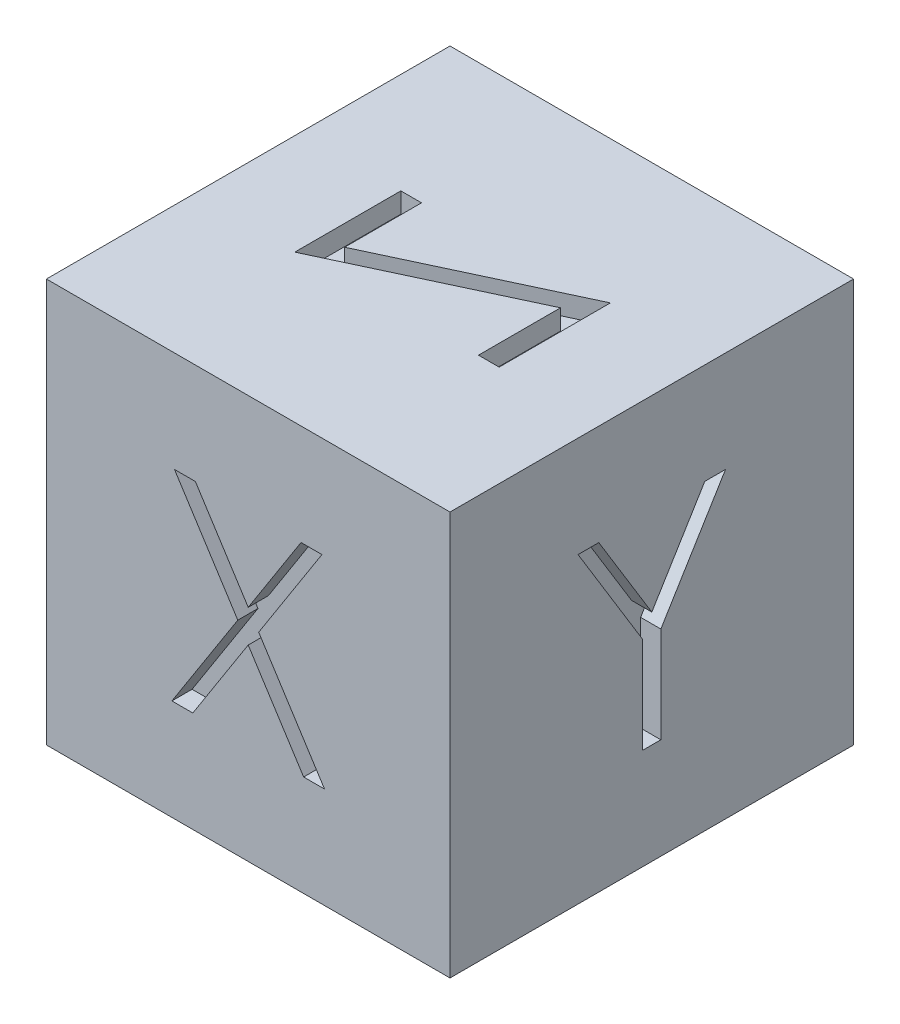
SolidWorks part; units mm, degrees
material "PET"
ref_plane "Front Plane" through (0, 0, 0) normal (0, 0, 1) x (1, 0, 0)
ref_plane "Top Plane" through (0, 0, 0) normal (0, 1, 0) x (1, 0, 0)
ref_plane "Right Plane" through (0, 0, 0) normal (1, 0, 0) x (0, 0, -1)
sketch "Sketch1" plane through (0, 0, 0) normal (0, 0, 1) x (1, 0, 0)
  line L1 (-10, -10) -> (10, -10)
  line L2 (-10, -10) -> (-10, 10)
  line L3 (-10, 10) -> (10, 10)
  line L4 (10, -10) -> (10, 10)
  line L5 (-10, -10) -> (10, 10) construction
  line L6 (-10, 10) -> (10, -10) construction
  point P0 (0, 0)
  dimension "D1" = 20
  dimension "D2" = 20
extrude "Boss-Extrude1" add sketch "Sketch1" along normal blind 20
sketch "Sketch2" plane through (0, 0, 20) normal (0, 0, 1) x (1, 0, 0)
  line L0 (-10, -5) -> (10, -5) construction
  line L1 (-10, 10) -> (-10, -10) construction
  line L2 (10, -10) -> (10, 10) construction
  text T0 "X" font "Century Gothic" height 10
  dimension "D1" = 5
extrude "X" cut sketch "Sketch2" against normal blind 1
sketch "Sketch3" plane through (10, 0, 0) normal (1, 0, 0) x (0, 0, -1)
  line L0 (-20, -5) -> (0, -5) construction
  line L1 (-20, -10) -> (-20, 10) construction
  line L2 (0, -10) -> (0, 10) construction
  text T0 "Y" font "Century Gothic" height 10
  dimension "D1" = 5
extrude "Y" cut sketch "Sketch3" against normal blind 1
sketch "Sketch4" plane through (0, 10, 0) normal (0, 1, 0) x (1, 0, 0)
  line L0 (5, 0) -> (5, -20) construction
  line L1 (10, 0) -> (-10, 0) construction
  line L2 (10, -20) -> (-10, -20) construction
  text T0 "Z" font "Century Gothic" height 10
  dimension "D1" = 5
extrude "Z" cut sketch "Sketch4" against normal blind 1
